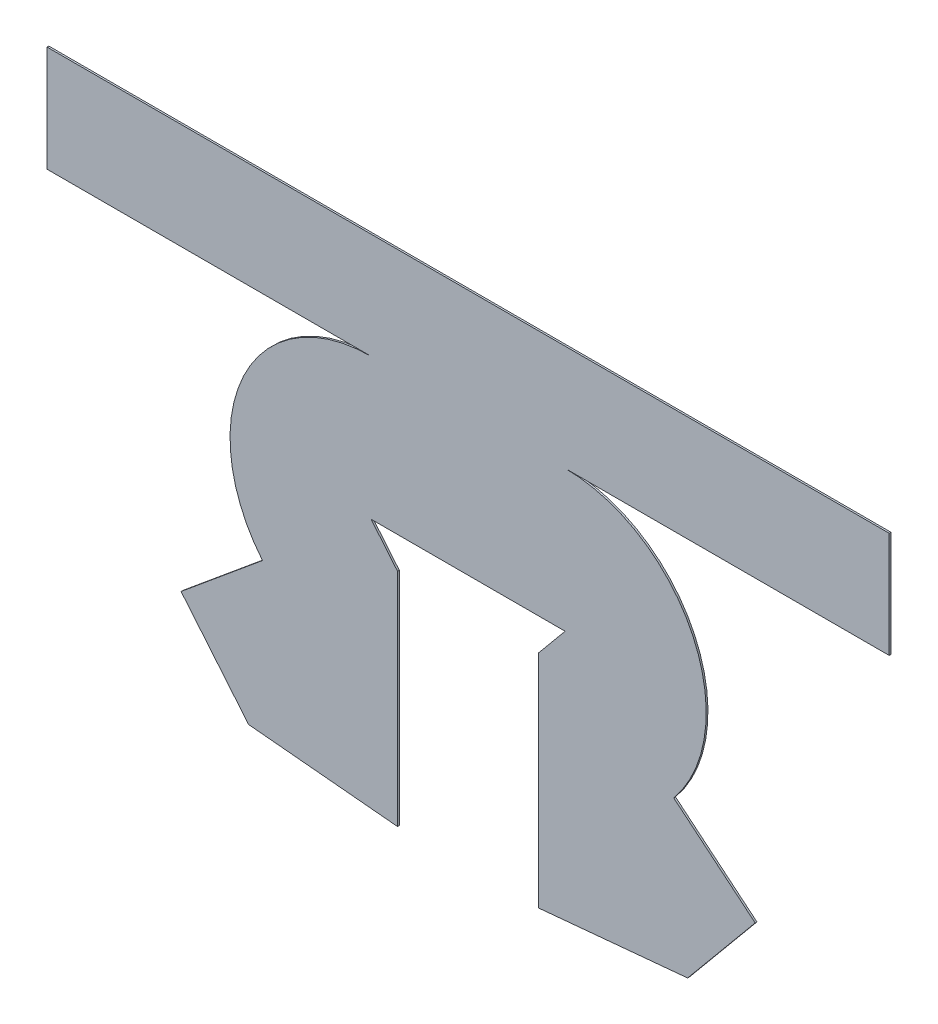
SolidWorks part; units mm, degrees
ref_plane "Front Plane" through (0, 0, 0) normal (0, 0, 1) x (1, 0, 0)
ref_plane "Top Plane" through (0, 0, 0) normal (0, 1, 0) x (1, 0, 0)
ref_plane "Right Plane" through (0, 0, 0) normal (1, 0, 0) x (0, 0, -1)
sketch "Sketch1" plane through (0, 0, 0) normal (0, 0, 1) x (1, 0, 0)
  line L0 (280.77, 169.165) -> (242.67, 123.2081)
  line L3 (1.37, 372.365) -> (280.77, 372.365)
  line L8 (1.37, 169.165) -> (39.47, 123.2081)
  line L11 (39.47, 169.165) -> (242.67, 169.165)
  line L13 (242.67, -195.1723) -> (242.67, 123.2081)
  line L17 (39.47, 123.2081) -> (39.47, -195.1723)
  line L20 (1.37, 169.165) -> (39.47, 169.165)
  line L21 (280.77, 169.165) -> (242.67, 169.165)
  line L22 (437.2026, 39.4766) -> (242.67, -195.1723)
  line L23 (1.37, 372.365) -> (280.77, 372.365)
  line L25 (-24.03, 524.765) -> (280.77, 524.765)
  line L27 (-24.03, 524.765) -> (-465.4695, 524.765)
  line L29 (1.37, 372.365) -> (-465.4695, 372.365)
  line L30 (-465.4695, 524.765) -> (-465.4695, 372.365)
  line L31 (-155.0626, 39.4766) -> (39.47, -195.1723)
  line L32 (-272.387, -57.7897) -> (-175.1207, -175.1141)
  line L33 (1.37, 372.365) -> (1.37, 169.165)
  line L34 (280.77, 372.365) -> (280.77, 169.165)
  line L36 (280.77, 372.365) -> (747.6096, 372.365)
  line L38 (280.77, 524.765) -> (747.6096, 524.765)
  line L39 (747.6096, 372.365) -> (747.6096, 524.765)
  line L42 (-175.1207, -175.1141) -> (39.47, -195.1723)
  line L43 (-272.387, -57.7897) -> (-155.0626, 39.4766)
  line L44 (554.5271, -57.7897) -> (457.2608, -175.1141)
  line L45 (457.2608, -175.1141) -> (242.67, -195.1723)
  line L46 (554.5271, -57.7897) -> (437.2026, 39.4766)
  arc A2 (1.37, 372.365) -> (-155.0626, 39.4766) centre (1.37, 169.165) ccw
  arc A3 (280.77, 372.365) -> (437.2026, 39.4766) centre (280.77, 169.165) cw
  dimension "D4" = 203.2
  dimension "D5" = 304.8
  dimension "D11" = 152.4
  dimension "D12" = 279.4
  dimension "D3" = 203.2
  dimension "D8" = 203.2
  dimension "D2" = 203.2
  dimension "D6" = 279.4
  dimension "D7" = 304.8
  dimension "D10" = 203.2
  dimension "D14" = 152.4
  dimension "D16" = 466.8396
  dimension "D19" = 152.4
extrude "Boss-Extrude2" add sketch "Sketch1" along normal blind 2.54 contours L34 L3 L33 L20 L11 L21 | L36 L39 L38 L25 L27 L30 L29 L3 | L33 A2 L31 L17 L8 | A3 L34 L0 L13 L22 | L44 L46 L22 L45 | L43 L32 L42 L31
